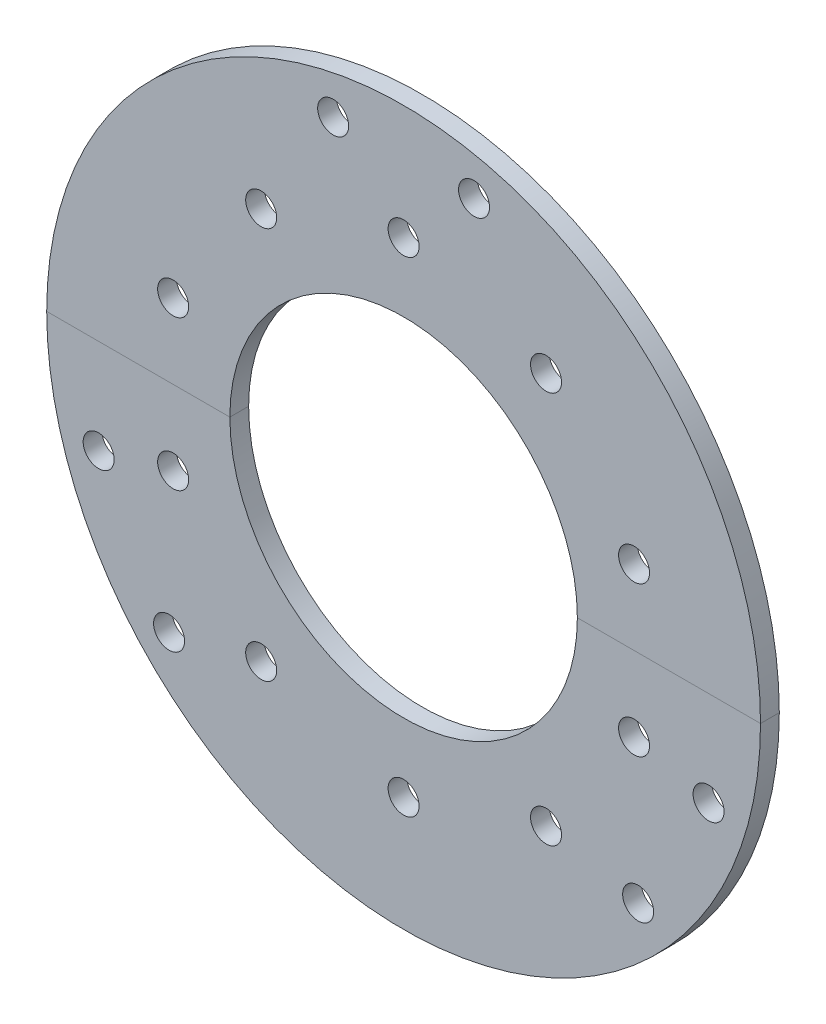
SolidWorks part; units mm, degrees
material "1060 Alloy"
ref_plane "Front Plane" through (0, 0, 0) normal (0, 0, 1) x (1, 0, 0)
ref_plane "Top Plane" through (0, 0, 0) normal (0, 1, 0) x (1, 0, 0)
ref_plane "Right Plane" through (0, 0, 0) normal (1, 0, 0) x (0, 0, -1)
sketch "Sketch1" plane through (0, 0, 0) normal (0, 0, 1) x (1, 0, 0)
  line L0 (0, 0) -> (0, 68) construction
  circle A0 centre (0, 0) radius 37
  circle A1 centre (0, 0) radius 76
  circle A2 centre (0, 0) radius 51.6 construction
  circle A3 centre (0, 51.6) radius 3.3
  circle A4 centre (30.3297, 41.7453) radius 3.3
  circle A5 centre (49.0745, 15.9453) radius 3.3
  circle A6 centre (49.0745, -15.9453) radius 3.3
  circle A7 centre (30.3297, -41.7453) radius 3.3
  circle A8 centre (0, -51.6) radius 3.3
  circle A9 centre (-30.3297, -41.7453) radius 3.3
  circle A10 centre (-49.0745, -15.9453) radius 3.3
  circle A11 centre (-49.0745, 15.9453) radius 3.3
  circle A12 centre (-30.3297, 41.7453) radius 3.3
  arc A13 (-15, 66.325) -> (15, 66.325) centre (0, 0) cw construction
  circle A14 centre (-15, 66.325) radius 3.3
  circle A15 centre (15, 66.325) radius 3.3
  circle A16 centre (64.9391, -20.1721) radius 3.3
  circle A17 centre (49.9391, -46.1529) radius 3.3
  circle A18 centre (-49.9391, -46.1529) radius 3.3
  circle A19 centre (-64.9391, -20.1721) radius 3.3
  point P9 (0, 68)
  point P28 (0, 0)
  point P43 (0, 0)
  dimension "InnerDiameter" = 74
  dimension "OuterDiamter" = 152
  dimension "FlangeBoltDiameter" = 103.2
  dimension "BoltClearanceHole" = 6.6
  dimension "LegStrutHoleRadius" = 68
  dimension "LegStrutHoleSeparation" = 30
  dimension "FlangeBoltNumber" = 10
  dimension "LegStrutNumber" = 3
extrude "Boss-Extrude1" add sketch "Sketch1" along normal blind 4
ref_plane "Plane1" through (0, 0, 0) normal (0, 1, 0) x (1, 0, 0)
split "Split1" trim tools "Plane1" bodies to split 101 resulting bodies 102 103
